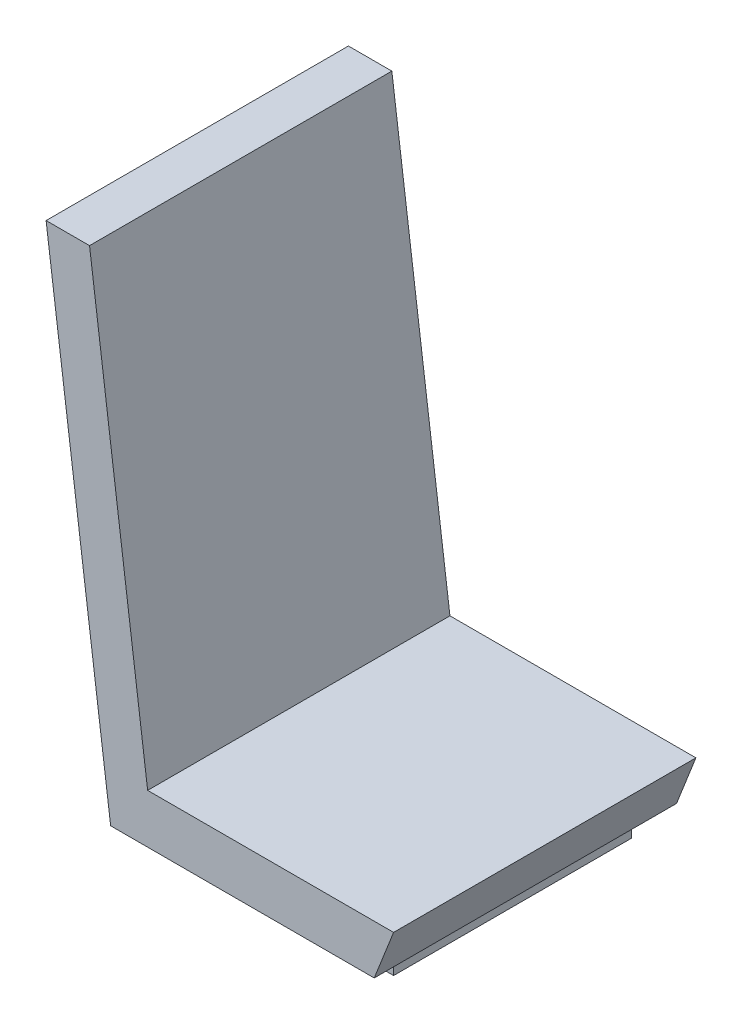
SolidWorks part; units mm, degrees
ref_plane "Front Plane" through (0, 0, 0) normal (0, 0, 1) x (1, 0, 0)
ref_plane "Top Plane" through (0, 0, 0) normal (0, 1, 0) x (1, 0, 0)
ref_plane "Right Plane" through (0, 0, 0) normal (1, 0, 0) x (0, 0, -1)
sketch "Sketch1" plane through (0, 0, 0) normal (0, 0, 1) x (1, 0, 0)
  line L0 (0, 0) -> (368.3, 0)
  line L1 (0, 0) -> (0, 31.75)
  line L2 (0, 31.75) -> (368.3, 31.75)
  line L3 (368.3, 31.75) -> (368.3, 0)
  dimension "D1" = 368.3
  dimension "D2" = 31.75
extrude "Boss-Extrude1" add sketch "Sketch1" along normal blind 368.3
shell "Shell1" thickness 31.75
sketch "Sketch2" plane through (0, 0, 0) normal (0, 0, 1) x (1, 0, 0)
  line L0 (368.3, 31.75) -> (388.3, 31.75)
  line L1 (388.3, 31.75) -> (418.3, 107.95)
  line L2 (418.3, 107.95) -> (37.3, 107.95)
  line L3 (0, 31.75) -> (-20, 31.75)
  line L4 (-20, 31.75) -> (-120, 793.75)
  line L5 (37.3, 107.95) -> (-52.7, 793.75)
  line L6 (-52.7, 793.75) -> (-120, 793.75)
  line L7 (0, 31.75) -> (368.3, 31.75)
  dimension "D1" = 20
  dimension "D2" = 20
  dimension "D3" = 100
  dimension "D4" = 762
  dimension "D5" = 30
  dimension "D6" = 76.2
  dimension "D7" = 381
extrude "Boss-Extrude2" add sketch "Sketch2" along normal blind 418.3 and the other way blind 50
